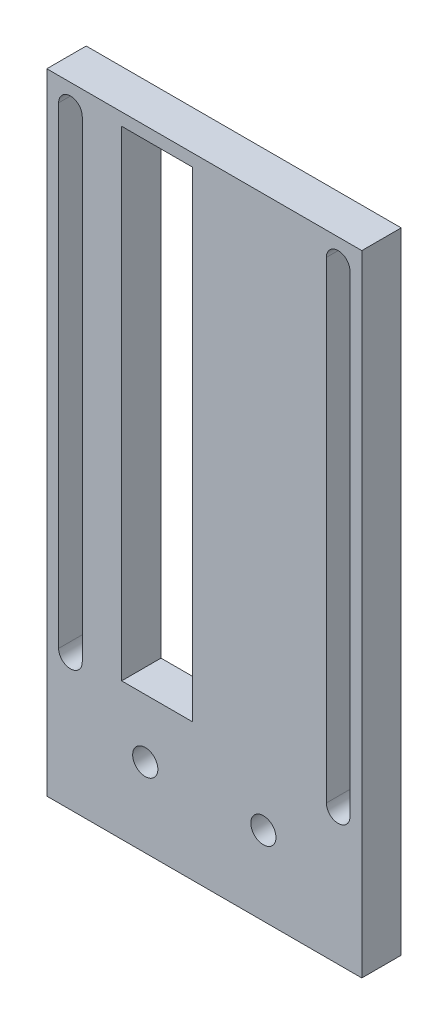
SolidWorks part; units mm, degrees
ref_plane "Front Plane" through (0, 0, 0) normal (0, 0, 1) x (1, 0, 0)
ref_plane "Top Plane" through (0, 0, 0) normal (0, 1, 0) x (1, 0, 0)
ref_plane "Right Plane" through (0, 0, 0) normal (1, 0, 0) x (0, 0, -1)
sketch "Sketch1" plane through (0, 0, 0) normal (0, 0, 1) x (1, 0, 0)
  line L0 (-7.5, 0) -> (7.5, 0) construction
  line L1 (-20, -10) -> (20, -10)
  line L2 (-20, -10) -> (-20, 10)
  line L3 (-20, 10) -> (20, 10)
  line L4 (20, -10) -> (20, 10)
  line L5 (-20, -10) -> (20, 10) construction
  line L6 (-20, 10) -> (20, -10) construction
  circle A0 centre (-7.5, 0) radius 1.6
  circle A1 centre (7.5, 0) radius 1.6
  point P0 (0, 0)
  point P10 (0, 0)
  dimension "D3" = 3.2
  dimension "D1" = 40
  dimension "D2" = 20
  dimension "D4" = 15
extrude "Boss-Extrude1" add sketch "Sketch1" along normal blind 5
sketch "Sketch2" plane through (0, -10, 0) normal (0, -1, 0) x (1, 0, 0)
  line L4 (-20, 0) -> (20, 0)
  line L5 (20, 0) -> (20, 5)
  line L6 (20, 5) -> (-20, 5)
  line L7 (-20, 5) -> (-20, 0)
  line L8 (-20, 0) -> (20, 0)
  line L9 (20, 0) -> (20, 5)
  line L10 (20, 5) -> (-20, 5)
  line L11 (-20, 5) -> (-20, 0)
  dimension "D1" = 0
sketch "Sketch3" plane through (0, 10, 0) normal (0, 1, 0) x (1, 0, 0)
  line L4 (20, 0) -> (-20, 0)
  line L5 (-20, 0) -> (-20, -5)
  line L6 (-20, -5) -> (20, -5)
  line L7 (20, -5) -> (20, 0)
  line L8 (20, 0) -> (-20, 0)
  line L9 (-20, 0) -> (-20, -5)
  line L10 (-20, -5) -> (20, -5)
  line L11 (20, -5) -> (20, 0)
  dimension "D1" = 0
extrude "Boss-Extrude3" add sketch "Sketch3" along normal blind 60
sketch "Sketch4" plane through (0, 0, 0) normal (0, 0, -1) x (-1, 0, 0)
  line L0 (-17, 67) -> (-17, 7) construction
  line L1 (-15.5, 67) -> (-15.5, 7)
  line L2 (-18.5, 67) -> (-18.5, 7)
  line L3 (17, 67) -> (17, 7) construction
  line L4 (18.5, 67) -> (18.5, 7)
  line L5 (15.5, 67) -> (15.5, 7)
  line L6 (-17, 37) -> (17, 37) construction
  line L7 (0, 70) -> (0, -10) construction
  line L8 (-20, 70) -> (20, 70) construction
  line L9 (-20, -10) -> (20, -10) construction
  arc A0 (-15.5, 67) -> (-18.5, 67) centre (-17, 67) ccw
  arc A1 (-18.5, 7) -> (-15.5, 7) centre (-17, 7) ccw
  arc A2 (18.5, 67) -> (15.5, 67) centre (17, 67) ccw
  arc A3 (15.5, 7) -> (18.5, 7) centre (17, 7) ccw
  point P2 (-17, 37)
  point P9 (17, 37)
  point P22 (0, 37)
  dimension "D2" = 3
  dimension "D5" = 3
  dimension "D1" = 34
  dimension "D3" = 3
  dimension "D4" = 60
extrude "Cut-Extrude1" cut sketch "Sketch4" against normal through all
sketch "Sketch5" plane through (0, 0, 0) normal (0, 0, -1) x (-1, 0, 0)
  line L0 (15.5, 67) -> (15.5, 7) construction
  line L1 (1.5, 7.4283) -> (10.5, 7.4283)
  line L2 (1.5, 7.4283) -> (1.5, 68.4256)
  line L3 (1.5, 68.4256) -> (10.5, 68.4256)
  line L4 (10.5, 7.4283) -> (10.5, 68.4256)
  line L5 (1.5, 7.4283) -> (10.5, 68.4256) construction
  line L6 (1.5, 68.4256) -> (10.5, 7.4283) construction
  point P0 (6, 37.927)
  dimension "D1" = 5
  dimension "D2" = 9
extrude "Cut-Extrude2" cut sketch "Sketch5" against normal through all
